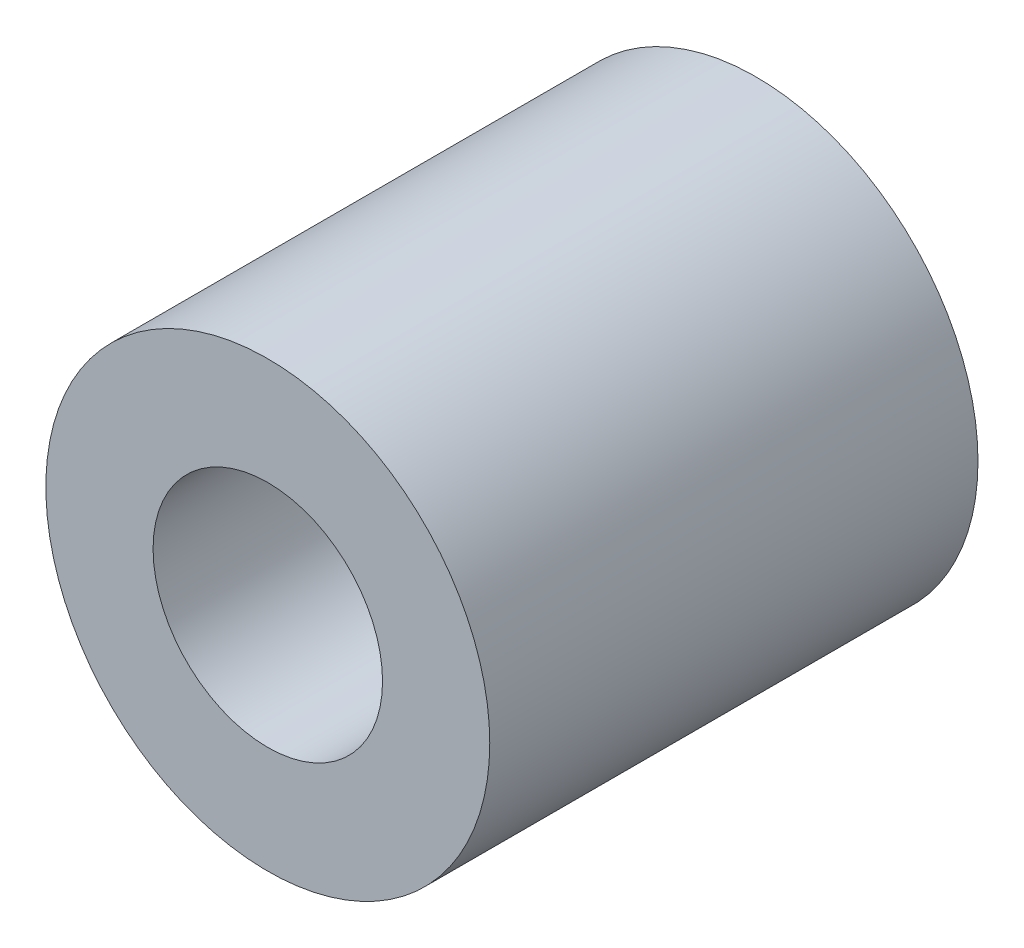
SolidWorks part; units mm, degrees
material "Cast Alloy Steel"
ref_plane "Front Plane" through (0, 0, 0) normal (0, 0, 1) x (1, 0, 0)
ref_plane "Top Plane" through (0, 0, 0) normal (0, 1, 0) x (1, 0, 0)
ref_plane "Right Plane" through (0, 0, 0) normal (1, 0, 0) x (0, 0, -1)
sketch "Sketch1" plane through (0, 0, 0) normal (0, 0, 1) x (1, 0, 0)
  circle A0 centre (0, 0) radius 18.185
  circle A1 centre (0, 0) radius 9.4
extrude "Boss-Extrude1" add sketch "Sketch1" along normal blind 40
